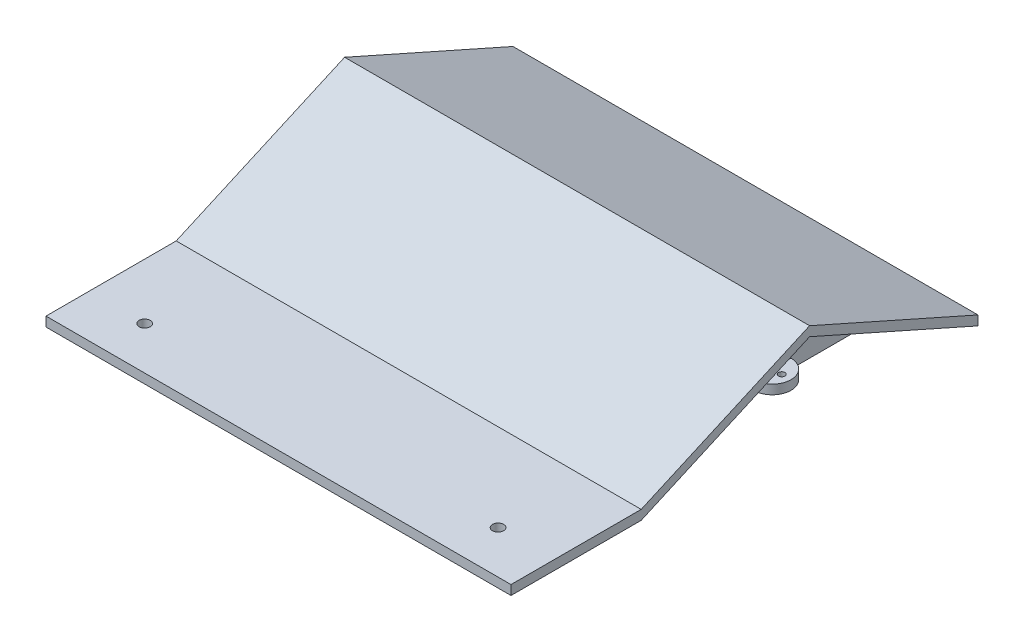
SolidWorks part; units mm, degrees
ref_plane "Front Plane" through (0, 0, 0) normal (0, 0, 1) x (1, 0, 0)
ref_plane "Top Plane" through (0, 0, 0) normal (0, 1, 0) x (1, 0, 0)
ref_plane "Right Plane" through (0, 0, 0) normal (1, 0, 0) x (0, 0, -1)
sketch "Sketch1" plane through (0, 0, 0) normal (1, 0, 0) x (0, 0, -1)
  line L0 (0, 0) -> (135, 0)
  line L1 (67.5, 0) -> (67.5, 30)
  line L2 (67.5, 30) -> (135, 0)
  line L3 (135, 0) -> (158.0421, -10.2409)
  line L4 (158.0421, -10.2409) -> (158.0421, -5.1205)
  line L5 (158.0421, -5.1205) -> (67.5, 35.1205)
  line L6 (67.5, 30) -> (0, 0)
  line L7 (0, 0) -> (-23.0421, -10.2409)
  line L8 (-23.0421, -10.2409) -> (-23.0421, -5.1205)
  line L9 (-23.0421, -5.1205) -> (67.5, 35.1205)
extrude "Boss-Extrude1" add sketch "Sketch1" against normal blind 250 contours L9 L8 L7 L6 L2 L3 L4 L5
sketch "Sketch2" plane through (0, 0, 0) normal (1, 0, 0) x (0, 0, -1)
  line L0 (0, 0) -> (135, 0)
  line L1 (67.5, 30) -> (158.0421, -10.2409) construction
  line L2 (135, 0) -> (67.5, 30)
  line L3 (67.5, 30) -> (0, 0)
extrude "Boss-Extrude2" add sketch "Sketch2" against normal blind 25
sketch "Sketch3" plane through (0, 0, 0) normal (1, 0, 0) x (0, 0, -1)
  line L0 (0, 0) -> (135, 0)
  line L1 (135, 0) -> (67.5, 30)
  line L2 (67.5, 30) -> (0, 0)
extrude "Cut-Extrude1" cut sketch "Sketch3" against normal blind 20
sketch "Sketch4" plane through (-250, 0, 0) normal (-1, 0, 0) x (0, 0, 1)
  line L0 (-135, 0) -> (0, 0)
  line L1 (0, 0) -> (-67.5, 30)
  line L2 (-67.5, 30) -> (-135, 0)
extrude "Boss-Extrude3" add sketch "Sketch4" against normal blind 25
sketch "Sketch5" plane through (-250, 0, 0) normal (-1, 0, 0) x (0, 0, 1)
  line L0 (-135, 0) -> (0, 0)
  line L1 (0, 0) -> (-67.5, 29.5827)
  line L2 (-67.5, 29.5827) -> (-135, 0)
extrude "Cut-Extrude2" cut sketch "Sketch5" against normal blind 20
sketch "Sketch6" plane through (0, 0, 0) normal (0, -1, 0) x (-1, 0, 0)
  line L0 (230, 67.5) -> (240, 67.5)
  circle A0 centre (230, 67.5) radius 10
  circle A1 centre (235, 67.5) radius 1.7
  line M1 (230, 0) -> (230, 135)
  line M3 (225, 135) -> (225, 0)
extrude "Boss-Extrude4" add sketch "Sketch6" against normal blind 5 contours A1 L0 A0 M1 | A1 L0 A0 M1 | A0 M3 | A0 M1 M3
sketch "Sketch7" plane through (0, 0, 0) normal (0, -1, 0) x (-1, 0, 0)
  line L0 (20, 67.5) -> (10, 67.5)
  circle A0 centre (20, 67.5) radius 10
  circle A1 centre (15, 67.5) radius 1.7
  line M1 (20, 135) -> (20, 0)
  line M3 (25, 0) -> (25, 135)
extrude "Boss-Extrude5" add sketch "Sketch7" against normal blind 5 contours A1 L0 A0 M1 | A1 L0 A0 M1 | A0 M1 M3 | A0 M3
sketch "Sketch8" plane through (-230, 0, 0) normal (-1, 0, 0) x (0, 0, 1)
  line L0 (-67.5, 5) -> (-67.5, 25)
  line L1 (-57.5, 5) -> (-77.5, 5) construction
  circle A0 centre (-67.5, 25) radius 1.5
extrude "Cut-Extrude3" cut sketch "Sketch8" against normal blind 10
sketch "Sketch9" plane through (-250, 0, 0) normal (-1, 0, 0) x (0, 0, 1)
  line L0 (23.0421, -5.1205) -> (93.0421, -5.1205)
  line L1 (93.0421, -5.1205) -> (93.0421, -10.2409)
  line L2 (93.0421, -10.2409) -> (23.0421, -10.2409)
  line L3 (23.0421, -10.2409) -> (23.0421, -5.1205)
extrude "Boss-Extrude7" add sketch "Sketch9" against normal blind 250
sketch "Sketch10" plane through (-250, 0, 0) normal (-1, 0, 0) x (0, 0, 1)
  line L0 (0, 0) -> (0, 5.1205)
  line L1 (23.0421, -5.1205) -> (-67.5, 35.1205) construction
  line L2 (0, 5.1205) -> (70, 5.1205)
  line L3 (70, 5.1205) -> (70, -5.1205)
  line L4 (93.0421, -5.1205) -> (23.0421, -5.1205) construction
  point P5 (0, 0)
sketch "Sketch11" plane through (0, -5.1205, 0) normal (0, 1, 0) x (1, 0, 0)
  line L0 (-250, -70) -> (-220, -70)
  line L1 (-250, 0) -> (-250, -70) construction
  line L2 (-250, -93.0421) -> (-250, -23.0421) construction
  line L3 (0, -70) -> (-30, -70)
  line L4 (0, -93.0421) -> (0, -23.0421) construction
  circle A0 centre (-220, -70) radius 3
  circle A1 centre (-30, -70) radius 3
extrude "Cut-Extrude4" cut sketch "Sketch11" against normal blind 10
